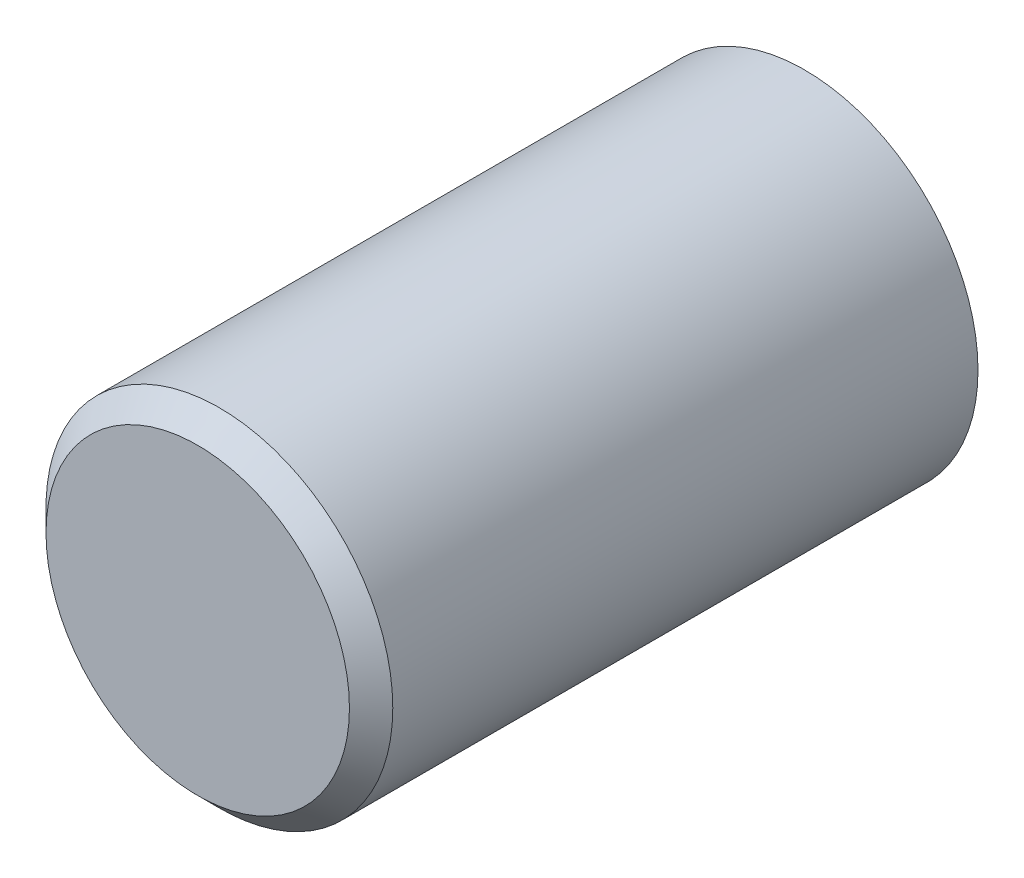
SolidWorks part; units mm, degrees
material "POM copolymère d'acétal"
ref_plane "Face" through (0, 0, 0) normal (0, 0, 1) x (1, 0, 0)
ref_plane "Dessus" through (0, 0, 0) normal (0, 1, 0) x (1, 0, 0)
ref_plane "Droite" through (0, 0, 0) normal (1, 0, 0) x (0, 0, -1)
sketch "Esquisse1" plane through (0, 0, 0) normal (0, 0, 1) x (1, 0, 0)
  circle A0 centre (0, 0) radius 4
extrude "Boss.-Extru.1" add sketch "Esquisse1" along normal blind 14
chamfer "Chanfrein1" distance 0.5 angle 45 1 edges at (4, 0, 14)
hole_wizard "Trou taraudé M41" positions "Esquisse3" profile "Esquisse2" tap size "M4" standard "Iso"
sketch "Esquisse3" plane through (0, 0, 0) normal (0, 0, -1) x (-1, 0, 0)
  point P2 (0, 0)
sketch "Esquisse2" plane through (0, 0, 0) normal (1, 0, 0) x (0, 1, 0)
  line L0 (0, 0) -> (0, 12.4914)
  line L1 (0, 12.4914) -> (1.65, 11.5)
  line L2 (1.65, 11.5) -> (1.65, 0)
  line L5 (1.65, 0) -> (0, 0)
  line L10 (0, 12.4914) -> (-1.65, 11.5) construction
  line L11 (0, -6.35) -> (0, 107.95) construction
  dimension "Diamètre du trou pour taraudage" = 3.3
  dimension "Profondeur du trou pour taraudage" = 11.5
  dimension "Angle de pointe" = 118
cosmetic thread "Filetage de perçage1" parameters "D1"=10, "D2"=4
